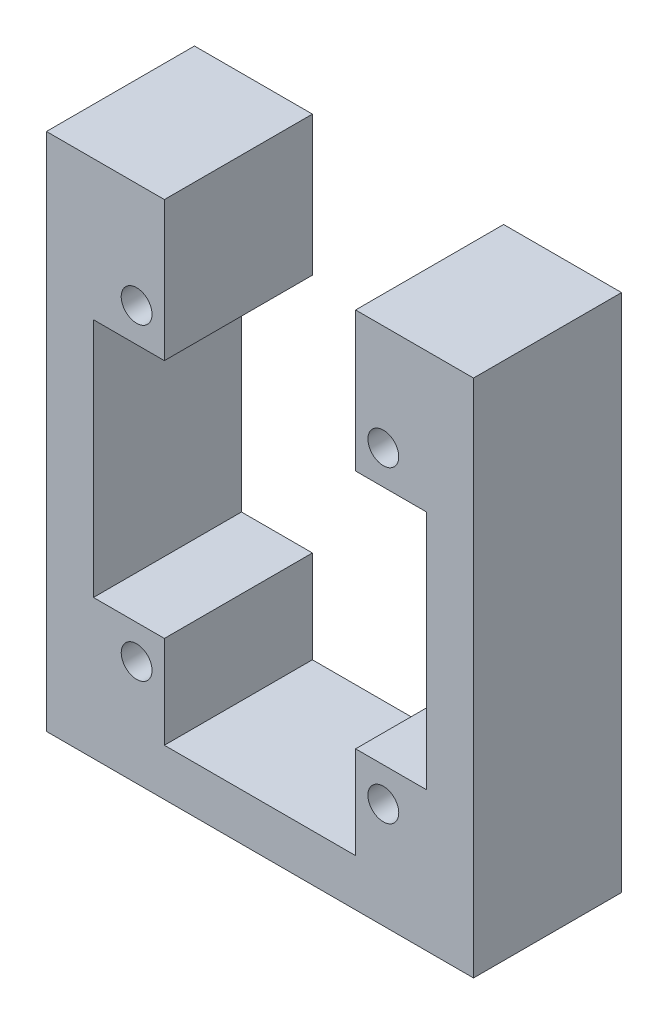
SolidWorks part; units mm, degrees
ref_plane "Front Plane" through (0, 0, 0) normal (0, 0, 1) x (1, 0, 0)
ref_plane "Top Plane" through (0, 0, 0) normal (0, 1, 0) x (1, 0, 0)
ref_plane "Right Plane" through (0, 0, 0) normal (1, 0, 0) x (0, 0, -1)
sketch "Sketch1" plane through (0, 0, 0) normal (0, 0, 1) x (1, 0, 0)
  line L1 (-13.5, -17.25) -> (13.5, -17.25)
  line L2 (-13.5, -17.25) -> (-13.5, 17.25)
  line L3 (-13.5, 17.25) -> (13.5, 17.25)
  line L4 (13.5, -17.25) -> (13.5, 17.25)
  line L5 (-13.5, -17.25) -> (13.5, 17.25) construction
  line L6 (-13.5, 17.25) -> (13.5, -17.25) construction
  line L7 (-17.31, -21.06) -> (17.31, -21.06)
  line L8 (-17.31, -21.06) -> (-17.31, 21.06)
  line L9 (-17.31, 21.06) -> (17.31, 21.06)
  line L10 (17.31, -21.06) -> (17.31, 21.06)
  line L11 (-17.31, -21.06) -> (17.31, 21.06) construction
  line L12 (-17.31, 21.06) -> (17.31, -21.06) construction
  point P0 (0, 0)
  point P6 (0, 0)
  dimension "D1" = 27
  dimension "D2" = 34.5
  dimension "D3" = 3.81
  dimension "D4" = 3.81
extrude "Boss-Extrude1" add sketch "Sketch1" along normal blind 12
sketch "Sketch2" plane through (0, 0, 0) normal (0, 0, -1) x (-1, 0, 0)
  line L0 (0, 17.25) -> (0, -17.25) construction
  line L1 (-13.5, 17.25) -> (-7.75, 17.25)
  line L2 (-13.5, 17.25) -> (-13.5, 9.75)
  line L3 (-13.5, 9.75) -> (-7.75, 9.75)
  line L4 (-7.75, 17.25) -> (-7.75, 9.75)
  line L5 (-13.5, 17.25) -> (13.5, 17.25) construction
  line L6 (13.5, -17.25) -> (-13.5, -17.25) construction
  line L7 (-13.5, 0) -> (13.5, 0) construction
  line L8 (-13.5, -17.25) -> (-13.5, 17.25) construction
  line L9 (13.5, 17.25) -> (13.5, -17.25) construction
  line L10 (13.5, 9.75) -> (7.75, 9.75)
  line L11 (7.75, 17.25) -> (7.75, 9.75)
  line L12 (13.5, 17.25) -> (7.75, 17.25)
  line L13 (13.5, 17.25) -> (13.5, 9.75)
  line L14 (13.5, -17.25) -> (13.5, -9.75)
  line L15 (13.5, -17.25) -> (7.75, -17.25)
  line L16 (7.75, -17.25) -> (7.75, -9.75)
  line L17 (13.5, -9.75) -> (7.75, -9.75)
  line L18 (-13.5, -9.75) -> (-7.75, -9.75)
  line L19 (-7.75, -17.25) -> (-7.75, -9.75)
  line L20 (-13.5, -17.25) -> (-7.75, -17.25)
  line L21 (-13.5, -17.25) -> (-13.5, -9.75)
  circle A0 centre (-10, 12.5) radius 1.25
  circle A1 centre (10, 12.5) radius 1.25
  circle A2 centre (10, -12.5) radius 1.25
  circle A3 centre (-10, -12.5) radius 1.25
  point P37 (-8.75, 12.5)
  point P38 (8.75, 12.5)
  point P39 (-10.4192, 14.5004)
  dimension "D5" = 2.5
  dimension "D1" = 5.75
  dimension "D2" = 20
  dimension "D3" = 25
  dimension "D4" = 7.5
extrude "Boss-Extrude2" add sketch "Sketch2" against normal through all
sketch "Sketch3" plane through (0, 0, 0) normal (0, 0, -1) x (-1, 0, 0)
  line L0 (-17.31, 21.06) -> (17.31, 21.06) construction
  line L1 (-7.75, 17.25) -> (7.75, 17.25)
  line L2 (-7.75, 17.25) -> (-7.75, 21.06)
  line L3 (-7.75, 21.06) -> (7.75, 21.06)
  line L4 (7.75, 17.25) -> (7.75, 21.06)
  line L5 (-7.75, 17.25) -> (7.75, 21.06) construction
  line L6 (-7.75, 21.06) -> (7.75, 17.25) construction
  line L7 (-7.75, 17.25) -> (7.75, 17.25) construction
  line L8 (-7.75, 9.75) -> (-7.75, 17.25) construction
  point P0 (0, 19.155)
  point P11 (0, 0)
extrude "Cut-Extrude1" cut sketch "Sketch3" against normal through all
